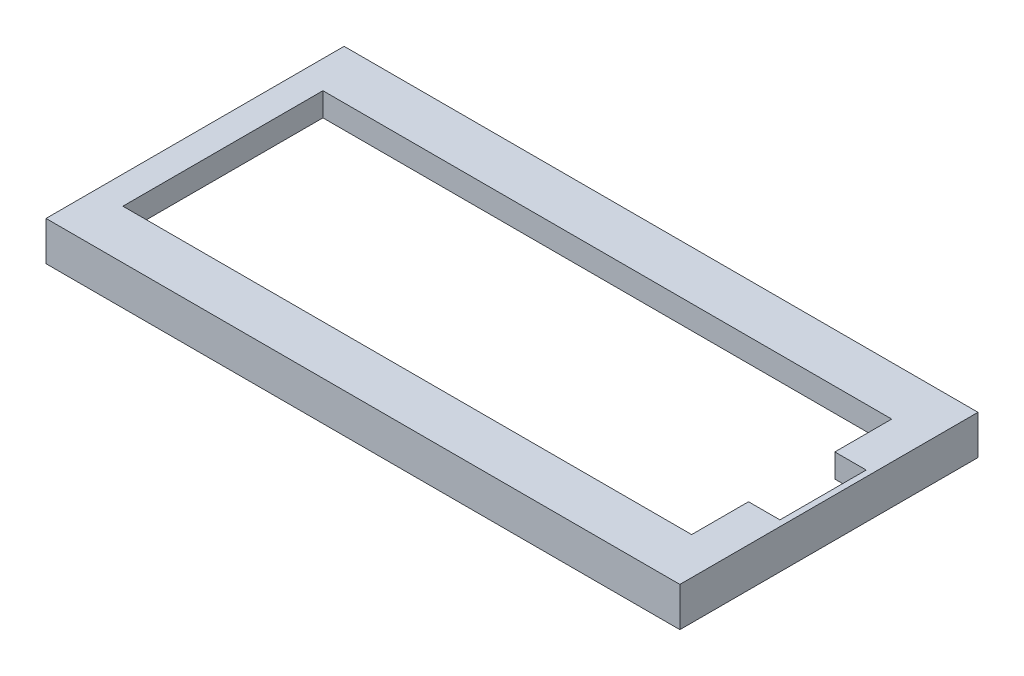
SolidWorks part; units mm, degrees
ref_plane "Front" through (0, 0, 0) normal (0, 0, 1) x (1, 0, 0)
ref_plane "Top" through (0, 0, 0) normal (0, 1, 0) x (1, 0, 0)
ref_plane "Right" through (0, 0, 0) normal (1, 0, 0) x (0, 0, -1)
sketch "Sketch1" plane through (0, 0, 0) normal (0, 1, 0) x (1, 0, 0)
  line L1 (41, -19) -> (-41, -19)
  line L2 (41, -19) -> (41, 19)
  line L3 (41, 19) -> (-41, 19)
  line L4 (-41, -19) -> (-41, 19)
  line L5 (41, -19) -> (-41, 19) construction
  line L6 (41, 19) -> (-41, -19) construction
  point P0 (0, 0)
  dimension "D1" = 38
  dimension "D2" = 82
extrude "main" add sketch "Sketch1" along normal blind 3
sketch "Sketch2" plane through (0, 3, 0) normal (0, 1, 0) x (1, 0, 0)
  line L1 (36.25, 12.75) -> (-36.25, 12.75)
  line L2 (36.25, 12.75) -> (36.25, -12.75)
  line L3 (36.25, -12.75) -> (-36.25, -12.75)
  line L4 (-36.25, 12.75) -> (-36.25, -12.75)
  line L5 (36.25, 12.75) -> (-36.25, -12.75) construction
  line L6 (36.25, -12.75) -> (-36.25, 12.75) construction
  point P0 (0, 0)
  dimension "D1" = 25.5
  dimension "D2" = 72.5
extrude "LCD cutout" cut sketch "Sketch2" against normal through all
sketch "Sketch3" plane through (0, 0, 0) normal (0, -1, 0) x (1, 0, 0)
  line L0 (41, -19) -> (-41, -19) construction
  line L1 (-35, -19) -> (6, -19)
  line L2 (-35, -19) -> (-35, -14.25)
  line L3 (-35, -14.25) -> (6, -14.25)
  line L4 (6, -19) -> (6, -14.25)
  line L5 (-41, -19) -> (-41, 19) construction
  line L6 (36.25, -12.75) -> (-36.25, -12.75) construction
  dimension "D1" = 1.5
  dimension "D2" = 6
  dimension "D3" = 41
extrude "connector cut" cut sketch "Sketch3" against normal blind 1.5
sketch "Sketch4" plane through (0, 3, 0) normal (0, 1, 0) x (1, 0, 0)
  line L1 (-41.5549, -5.5) -> (41.5549, -5.5) construction
  line L2 (-41.5549, -5.5) -> (-41.5549, 5.5) construction
  line L3 (-41.5549, 5.5) -> (41.5549, 5.5) construction
  line L4 (41.5549, -5.5) -> (41.5549, 5.5) construction
  line L5 (-41.5549, -5.5) -> (41.5549, 5.5) construction
  line L6 (-41.5549, 5.5) -> (41.5549, -5.5) construction
  line L7 (41.5549, 5.5) -> (32.2219, 5.5)
  line L8 (41.5549, 5.5) -> (41.5549, -5.5)
  line L9 (41.5549, -5.5) -> (32.2219, -5.5)
  line L10 (32.2219, 5.5) -> (32.2219, -5.5)
  point P0 (0, 0)
  dimension "D1" = 11
extrude "Cut-Extrude3" cut sketch "Sketch4" against normal through all
sketch "Sketch5" plane through (0, 0, 0) normal (0, 1, 0) x (1, 0, 0)
  line L1 (-43.2099, -1.5) -> (43.2099, -1.5) construction
  line L2 (-43.2099, -1.5) -> (-43.2099, 1.5) construction
  line L3 (-43.2099, 1.5) -> (43.2099, 1.5) construction
  line L4 (43.2099, -1.5) -> (43.2099, 1.5) construction
  line L5 (-43.2099, -1.5) -> (43.2099, 1.5) construction
  line L6 (-43.2099, 1.5) -> (43.2099, -1.5) construction
  line L7 (43.2099, 1.5) -> (34.4214, 1.5)
  line L8 (43.2099, 1.5) -> (43.2099, -1.5)
  line L9 (43.2099, -1.5) -> (34.4214, -1.5)
  line L10 (34.4214, 1.5) -> (34.4214, -1.5)
  point P0 (0, 0)
  dimension "D1" = 3
extrude "Cut-Extrude5" [suppressed] cut sketch "Sketch5" along normal through all
sketch "Sketch6" plane through (0, 0, 0) normal (0, 1, 0) x (1, 0, 0)
  line L1 (41, -19) -> (-41, -19)
  line L2 (41, -19) -> (41, 19)
  line L3 (41, 19) -> (-41, 19)
  line L4 (-41, -19) -> (-41, 19)
  line L5 (41, -19) -> (-41, 19) construction
  line L6 (41, 19) -> (-41, -19) construction
  point P0 (0, 0)
extrude "Boss-Extrude2" add sketch "Sketch6" against normal blind 2
sketch "Sketch7" plane through (0, 0, 0) normal (0, 1, 0) x (1, 0, 0)
  line L1 (40.25, -18.25) -> (-40.25, -18.25)
  line L2 (40.25, -18.25) -> (40.25, 18.25)
  line L3 (40.25, 18.25) -> (-40.25, 18.25)
  line L4 (-40.25, -18.25) -> (-40.25, 18.25)
  line L5 (40.25, -18.25) -> (-40.25, 18.25) construction
  line L6 (40.25, 18.25) -> (-40.25, -18.25) construction
  point P0 (0, 0)
  dimension "D1" = 36.5
  dimension "D2" = 80.5
extrude "Cut-Extrude6" cut sketch "Sketch7" against normal through all
sketch "Sketch8" plane through (0, 1.5, 0) normal (0, -1, 0) x (1, 0, 0)
  line L0 (41, -19) -> (-41, -19) construction
  line L1 (6, -14.25) -> (-35, -14.25)
  line L2 (6, -14.25) -> (6, -19)
  line L3 (6, -19) -> (-35, -19)
  line L4 (-35, -14.25) -> (-35, -19)
  line L5 (-35, -14.25) -> (-35, -19) construction
extrude "Cut-Extrude7" cut sketch "Sketch8" along normal through all
sketch "Sketch9" plane through (0, 0, 0) normal (0, 1, 0) x (1, 0, 0)
  line L1 (40.25, 5.5) -> (41, 5.5)
  line L2 (40.25, 5.5) -> (40.25, -5.5)
  line L3 (40.25, -5.5) -> (41, -5.5)
  line L4 (41, 5.5) -> (41, -5.5)
extrude "Boss-Extrude3" add sketch "Sketch9" along normal up to vertex (3 mm away)
sketch "Sketch10" plane through (-41, 0, 0) normal (-1, 0, 0) x (0, 0, 1)
  line L1 (-19, -2) -> (19, -2)
  line L2 (-19, -2) -> (-19, 3)
  line L3 (-19, 3) -> (19, 3)
  line L4 (19, -2) -> (19, 3)
extrude "Cut-Extrude8" cut sketch "Sketch10" against normal blind 1.2
